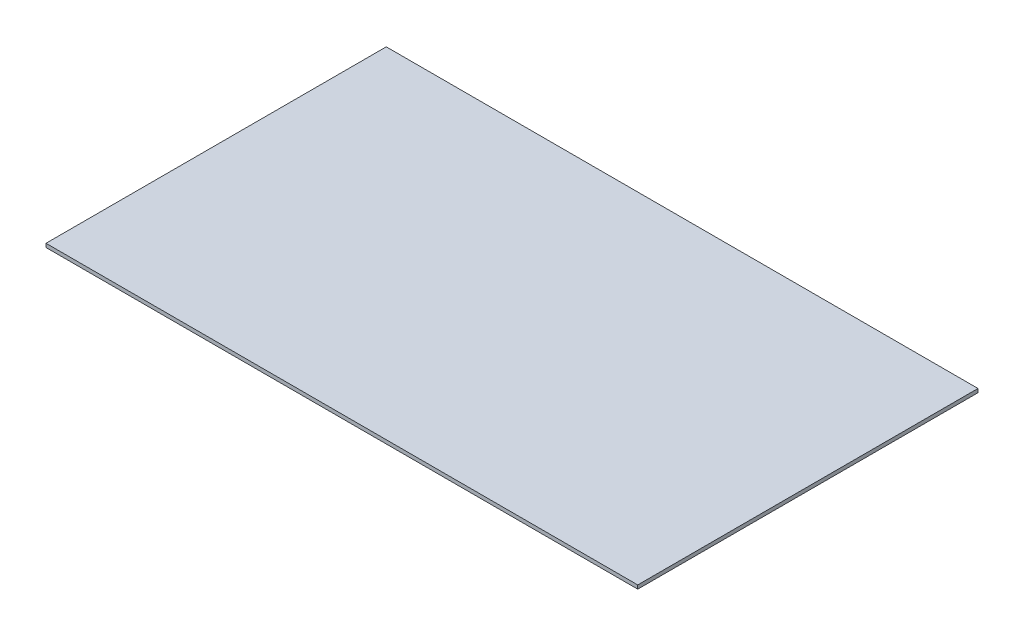
SolidWorks part; units mm, degrees
ref_plane "Front Plane" through (0, 0, 0) normal (0, 0, 1) x (1, 0, 0)
ref_plane "Top Plane" through (0, 0, 0) normal (0, 1, 0) x (1, 0, 0)
ref_plane "Right Plane" through (0, 0, 0) normal (1, 0, 0) x (0, 0, -1)
sketch "Sketch1" plane through (0, 0, 0) normal (0, 1, 0) x (1, 0, 0)
  line L1 (-98.6478, 73.3453) -> (155.3522, 73.3453)
  line L2 (-98.6478, 73.3453) -> (-98.6478, -72.7047)
  line L3 (-98.6478, -72.7047) -> (155.3522, -72.7047)
  line L4 (155.3522, 73.3453) -> (155.3522, -72.7047)
  dimension "D1" = 146.05
  dimension "D2" = 254
extrude "Boss-Extrude1" add sketch "Sketch1" along normal blind 1.5875
